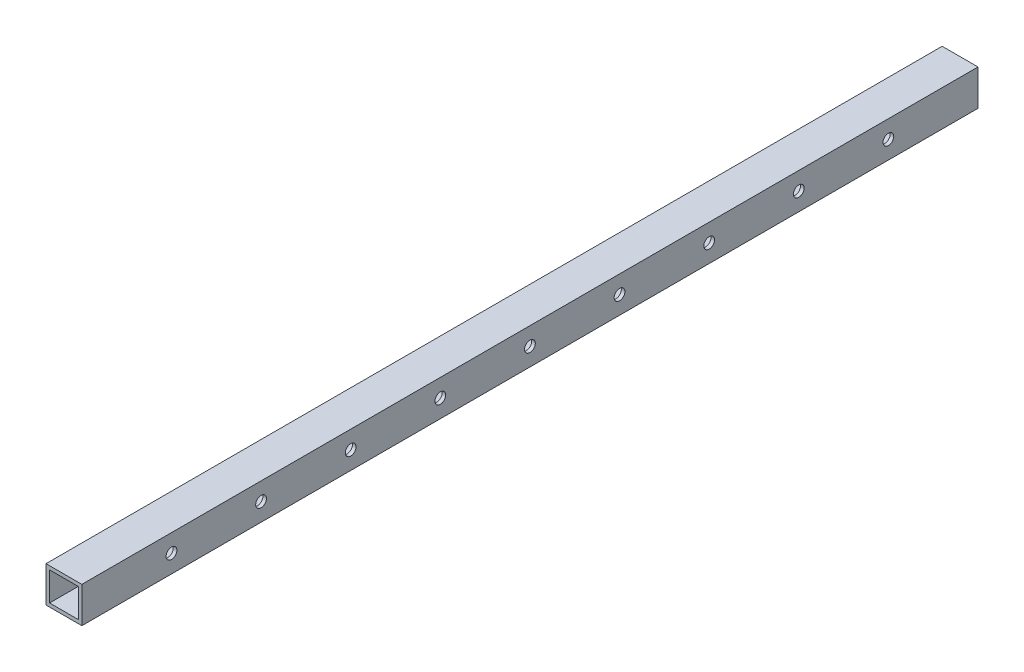
SolidWorks part; units mm, degrees
material "1060 Alloy"
ref_plane "Front Plane" through (0, 0, 0) normal (0, 0, 1) x (1, 0, 0)
ref_plane "Top Plane" through (0, 0, 0) normal (0, 1, 0) x (1, 0, 0)
ref_plane "Right Plane" through (0, 0, 0) normal (1, 0, 0) x (0, 0, -1)
sketch "Sketch1" plane through (0, 0, 0) normal (0, 0, 1) x (1, 0, 0)
  line L1 (-8, 8) -> (8, 8)
  line L2 (-8, 8) -> (-8, -8)
  line L3 (-8, -8) -> (8, -8)
  line L4 (8, 8) -> (8, -8)
  line L5 (-8, 8) -> (8, -8) construction
  line L6 (-8, -8) -> (8, 8) construction
  line L7 (-10, 10) -> (10, 10)
  line L8 (-10, 10) -> (-10, -10)
  line L9 (-10, -10) -> (10, -10)
  line L10 (10, 10) -> (10, -10)
  line L11 (-10, 10) -> (10, -10) construction
  line L12 (-10, -10) -> (10, 10) construction
  point P0 (0, 0)
  point P6 (0, 0)
  dimension "D1" = 20
  dimension "D2" = 16
  dimension "D3" = 20
  dimension "D4" = 16
extrude "Boss-Extrude1" add sketch "Sketch1" along normal blind 500
ref_plane "Plane1" through (0, 0, 250) normal (0, 0, 1) x (1, 0, 0)
sketch "Sketch3" plane through (-10, 0, 0) normal (-1, 0, 0) x (0, 0, 1)
  circle A0 centre (50, 0) radius 3
  dimension "D1" = 6
  dimension "D2" = 50
extrude "Cut-Extrude1" cut sketch "Sketch3" against normal through all
pattern_linear "LPattern1" count 9 spacing 50 along (0, 0, 1) of "Cut-Extrude1"
